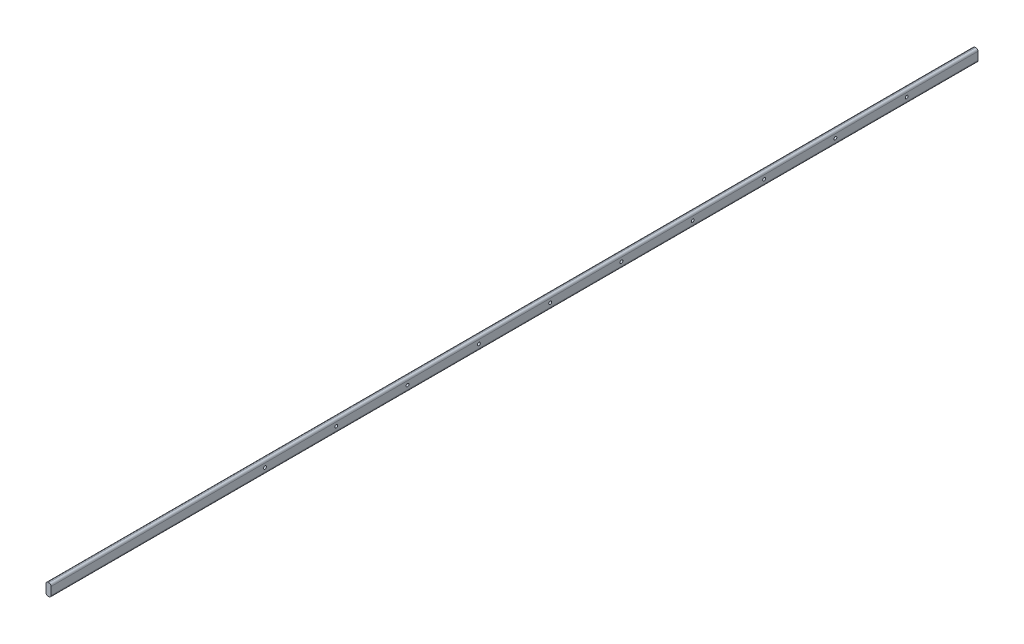
SolidWorks part; units mm, degrees
ref_plane "前视基准面" through (0, 0, 0) normal (0, 0, 1) x (1, 0, 0)
ref_plane "上视基准面" through (0, 0, 0) normal (0, 1, 0) x (1, 0, 0)
ref_plane "右视基准面" through (0, 0, 0) normal (1, 0, 0) x (0, 0, -1)
sketch "草图2" plane through (0, 0, 0) normal (0, 0, 1) x (1, 0, 0)
  line L1 (-0.5, 8.5) -> (0.5, 8.5)
  line L2 (-3.5, 5.5) -> (-3.5, -5.5)
  line L3 (-0.5, -8.5) -> (0.5, -8.5)
  line L4 (3.5, 5.5) -> (3.5, -5.5)
  line L5 (-3.5, 8.5) -> (3.5, -8.5) construction
  line L6 (-3.5, -8.5) -> (3.5, 8.5) construction
  arc A0 (0.5, 8.5) -> (3.5, 5.5) centre (0.5, 5.5) cw
  arc A1 (-0.5, 8.5) -> (-3.5, 5.5) centre (-0.5, 5.5) ccw
  arc A2 (-3.5, -5.5) -> (-0.5, -8.5) centre (-0.5, -5.5) ccw
  arc A3 (0.5, -8.5) -> (3.5, -5.5) centre (0.5, -5.5) ccw
  point P0 (0, 0)
  point P17 (3.5, 0)
  point P18 (0, 0)
  dimension "D1" = 3
  dimension "D2" = 3
  dimension "D3" = 3
  dimension "D4" = 3
  dimension "D5" = 1
  dimension "D6" = 5.5
extrude "凸台-拉伸1" add sketch "草图2" along normal blind 1300
sketch "草图3" plane through (-3.5, 0, 0) normal (-1, 0, 0) x (0, 0, 1)
  circle A0 centre (100, 0) radius 2
  circle A1 centre (200, 0) radius 2
  circle A2 centre (300, 0) radius 2
  circle A3 centre (400, 0) radius 2
  circle A4 centre (500, 0) radius 2
  circle A5 centre (600, 0) radius 2
  circle A6 centre (700, 0) radius 2
  circle A7 centre (800, 0) radius 2
  circle A8 centre (900, 0) radius 2
  circle A9 centre (1000, 0) radius 2
extrude "切除-拉伸1" cut sketch "草图3" against normal through all
